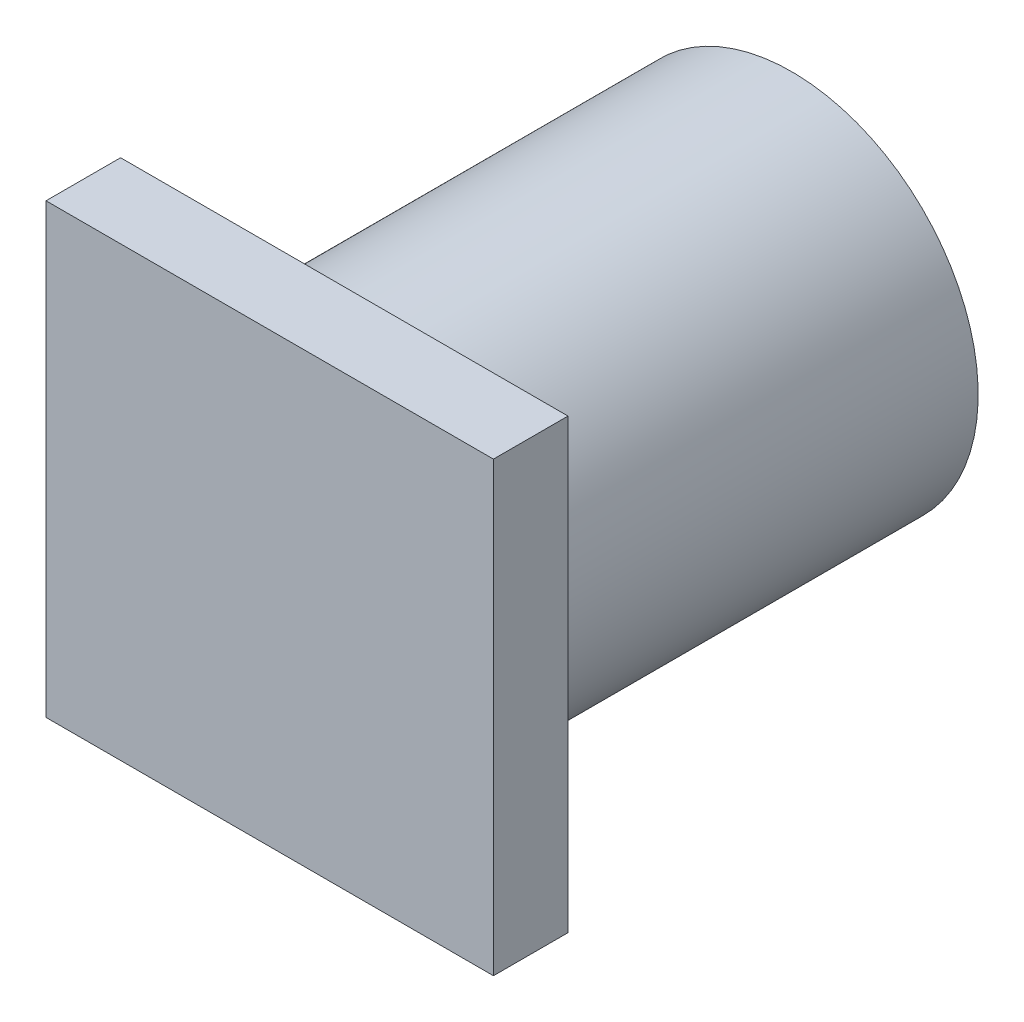
SolidWorks part; units mm, degrees
ref_plane "Plan de face" through (0, 0, 0) normal (0, 0, 1) x (1, 0, 0)
ref_plane "Plan de dessus" through (0, 0, 0) normal (0, 1, 0) x (1, 0, 0)
ref_plane "Plan de droite" through (0, 0, 0) normal (1, 0, 0) x (0, 0, -1)
sketch "Esquisse1" plane through (0, 0, 0) normal (0, 0, 1) x (1, 0, 0)
  line L5 (-6, -6) -> (6, -6)
  line L6 (-6, -6) -> (-6, 6)
  line L7 (-6, 6) -> (6, 6)
  line L8 (6, -6) -> (6, 6)
  line L9 (-6, -6) -> (6, 6) construction
  line L10 (-6, 6) -> (6, -6) construction
  point P0 (0, 0)
  dimension "D1" = 12
  dimension "D2" = 12
extrude "Boss.-Extru.1" add sketch "Esquisse1" along normal blind 2
sketch "Esquisse3" plane through (0, 0, 0) normal (0, 0, -1) x (-1, 0, 0)
  circle A0 centre (0, 0) radius 5
  dimension "D1" = 10
extrude "Boss.-Extru.2" add sketch "Esquisse3" along normal blind 12
sketch "Esquisse4" plane through (0, 0, -12) normal (0, 0, -1) x (-1, 0, 0)
  line L0 (5, 0) -> (0, 0) construction
  line L1 (0, 0) -> (0, 5) construction
  circle A0 centre (0, 0) radius 5 construction
  circle A1 centre (0, 0) radius 5 construction
ref_plane "Plan2" through (0, 0, -12) normal (1, 0, 0) x (0, 0, -1)
ref_plane "Plan3" through (0, 0, -12) normal (0, 1, 0) x (1, 0, 0)
